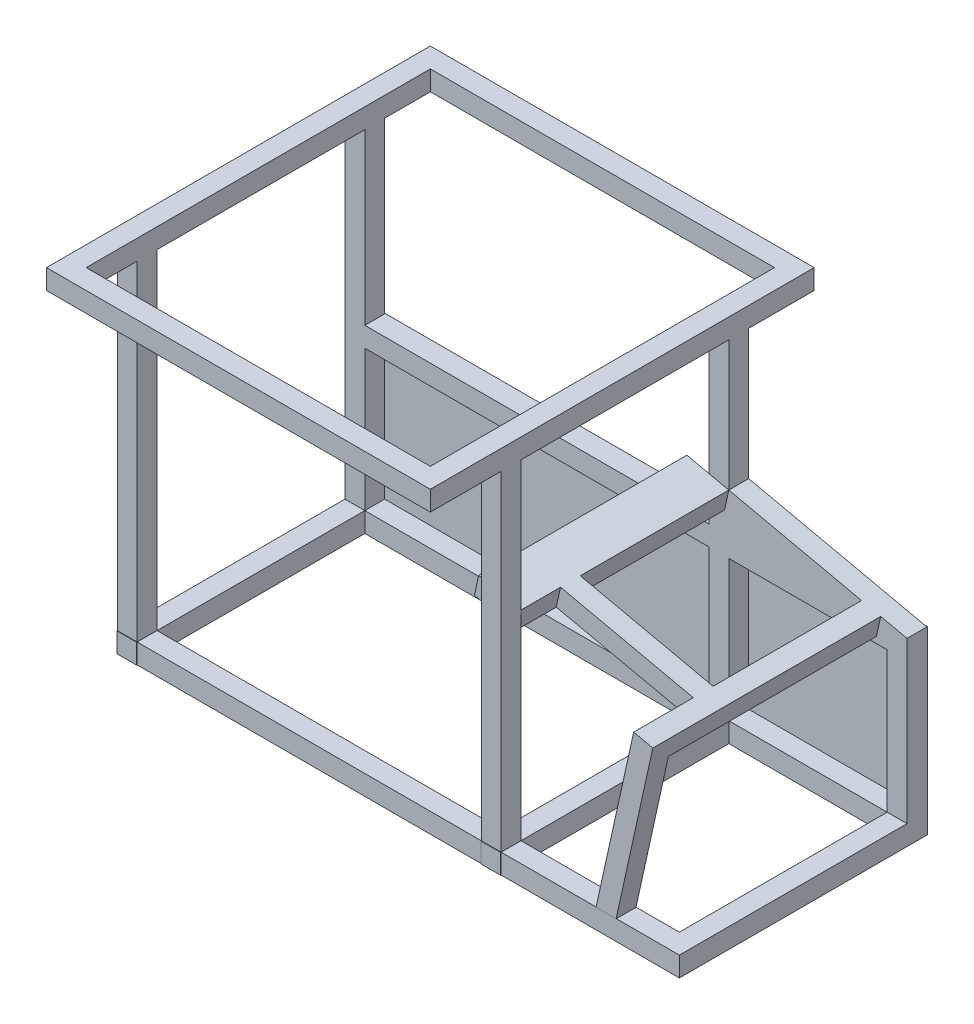
SolidWorks part; units mm, degrees
ref_plane "Front" through (0, 0, 0) normal (0, 0, 1) x (1, 0, 0)
ref_plane "Top" through (0, 0, 0) normal (0, 1, 0) x (1, 0, 0)
ref_plane "Right" through (0, 0, 0) normal (1, 0, 0) x (0, 0, -1)
sketch "Croquis1" plane through (0, 0, 0) normal (0, 1, 0) x (1, 0, 0)
  line L0 (-25.4, -25.4) -> (-25.4, 465.9875)
  line L1 (0, 0) -> (440.5875, 0)
  line L2 (0, 0) -> (0, 440.5875)
  line L3 (0, 440.5875) -> (440.5875, 440.5875)
  line L4 (440.5875, 0) -> (440.5875, 440.5875)
  line L5 (-25.4, 465.9875) -> (465.9875, 465.9875)
  line L6 (465.9875, -25.4) -> (465.9875, 465.9875)
  line L7 (-25.4, -25.4) -> (465.9875, -25.4)
  dimension "D2" = 440.5875
  dimension "D3" = 440.5875
  dimension "D1" = 25.4
extrude "Saliente-Extruir1" add sketch "Croquis1" against normal blind 25.4
sketch "Croquis2" plane through (0, -25.4, 0) normal (0, -1, 0) x (1, 0, 0)
  line L10 (-25.4, -382.0875) -> (465.9875, -382.0875) construction
  line L11 (465.9875, -382.0875) -> (440.5875, -382.0875)
  line L12 (465.9875, -382.0875) -> (465.9875, -356.6875)
  line L13 (465.9875, -356.6875) -> (440.5875, -356.6875)
  line L14 (440.5875, -382.0875) -> (440.5875, -356.6875)
  line L15 (-25.4, -356.6875) -> (0, -356.6875)
  line L16 (-25.4, -356.6875) -> (-25.4, -382.0875)
  line L17 (-25.4, -382.0875) -> (0, -382.0875)
  line L18 (0, -356.6875) -> (0, -382.0875)
  line L19 (-25.4, -465.9875) -> (-25.4, 25.4) construction
  line L20 (465.9875, 25.4) -> (465.9875, -465.9875) construction
  dimension "D1" = 25.4
extrude "Saliente-Extruir2" add sketch "Croquis2" along normal up to surface (422.3129 mm away)
sketch "Croquis3" plane through (0, -447.7129, 0) normal (0, -1, 0) x (1, 0, 0)
  line L1 (-25.4, -382.0875) -> (0, -382.0875)
  line L2 (-25.4, -382.0875) -> (-25.4, -356.6875)
  line L3 (-25.4, -356.6875) -> (0, -356.6875)
  line L4 (0, -382.0875) -> (0, -356.6875)
  line L5 (465.9875, -382.0875) -> (440.5875, -382.0875)
  line L6 (465.9875, -382.0875) -> (465.9875, -356.6875)
  line L7 (465.9875, -356.6875) -> (440.5875, -356.6875)
  line L8 (440.5875, -382.0875) -> (440.5875, -356.6875)
  line L14 (-25.4, -382.0875) -> (465.9875, -382.0875) construction
extrude "Saliente-Extruir3" add sketch "Croquis3" along normal blind 25.4
sketch "Croquis4" plane through (0, 0, 0) normal (1, 0, 0) x (0, 0, -1)
  line L0 (382.0875, -473.1129) -> (382.0875, -25.4) construction
  line L1 (356.6875, -473.1129) -> (382.0875, -473.1129)
  line L2 (356.6875, -473.1129) -> (356.6875, -447.7129)
  line L3 (356.6875, -447.7129) -> (382.0875, -447.7129)
  line L4 (382.0875, -473.1129) -> (382.0875, -447.7129)
  dimension "D1" = 25.4
extrude "Saliente-Extruir4" add sketch "Croquis4" along normal up to next
sketch "Croquis5" plane through (0, 0, -356.6875) normal (0, 0, 1) x (1, 0, 0)
  line L1 (0, -447.7129) -> (-25.4, -447.7129)
  line L2 (0, -447.7129) -> (0, -473.1129)
  line L3 (0, -473.1129) -> (-25.4, -473.1129)
  line L4 (-25.4, -447.7129) -> (-25.4, -473.1129)
  line L5 (440.5875, -447.7129) -> (465.9875, -447.7129)
  line L6 (440.5875, -447.7129) -> (440.5875, -473.1129)
  line L7 (440.5875, -473.1129) -> (465.9875, -473.1129)
  line L8 (465.9875, -447.7129) -> (465.9875, -473.1129)
extrude "Saliente-Extruir5" add sketch "Croquis5" along normal blind 292
sketch "Croquis6" plane through (440.5875, 0, 0) normal (-1, 0, 0) x (0, 0, 1)
  line L2 (0, -399) -> (25.4, -399)
  line L3 (0, -399) -> (0, -424.4)
  line L4 (0, -424.4) -> (25.4, -424.4)
  line L5 (25.4, -399) -> (25.4, -424.4)
sketch "Croquis7" plane through (0, 0, 0) normal (1, 0, 0) x (0, 0, -1)
  line L0 (356.6875, -447.7129) -> (356.6875, -25.4) construction
  line L1 (356.6875, -267.7129) -> (382.0875, -267.7129)
  line L2 (356.6875, -267.7129) -> (356.6875, -242.3129)
  line L3 (356.6875, -242.3129) -> (382.0875, -242.3129)
  line L4 (382.0875, -267.7129) -> (382.0875, -242.3129)
  line L5 (382.0875, -447.7129) -> (382.0875, -25.4) construction
  line L6 (382.0875, -447.7129) -> (356.6875, -447.7129) construction
  dimension "D1" = 25.4
  dimension "D2" = 180
extrude "Saliente-Extruir7" add sketch "Croquis7" along normal up to next
sketch "Croquis9" plane through (0, -447.7129, 0) normal (0, 1, 0) x (1, 0, 0)
  line L0 (465.9875, 382.0875) -> (694.1478, 382.0875)
  line L1 (694.1478, 382.0875) -> (694.1478, 65.2424)
  line L2 (694.1478, 65.2424) -> (465.9875, 65.2424)
  line L3 (465.9875, 64.6875) -> (465.9875, 356.6875) construction
  line L4 (465.9875, 356.6875) -> (668.7478, 356.6875)
  line L5 (668.7478, 356.6875) -> (668.7478, 90.6424)
  line L6 (668.7478, 90.6424) -> (465.9875, 90.6424)
  line L8 (465.9875, 356.6875) -> (465.9875, 382.0875)
  line L9 (465.9875, 90.6424) -> (0, 90.6424)
  line L10 (0, 440.5875) -> (0, 0) construction
  line L11 (0, 90.6424) -> (0, 65.2424)
  line L12 (0, 65.2424) -> (465.9875, 65.2424)
  dimension "D1" = 25.4
extrude "Saliente-Extruir9" add sketch "Croquis9" against normal blind 25.4
sketch "Croquis10" plane through (0, 0, -356.6875) normal (0, 0, 1) x (1, 0, 0)
  line L0 (668.7478, -447.7129) -> (668.7478, -267.7129)
  line L1 (668.7478, -267.7129) -> (465.9875, -267.7129)
  line L2 (465.9875, -267.7129) -> (465.9875, -191.9475)
  line L3 (465.9875, -447.7129) -> (465.9875, -25.4) construction
  line L4 (465.9875, -191.9475) -> (694.1478, -242.3129)
  line L5 (694.1478, -242.3129) -> (694.1478, -447.7129)
  line L6 (694.1478, -447.7129) -> (668.7478, -447.7129)
extrude "Saliente-Extruir10" add sketch "Croquis10" against normal blind 25.4
sketch "Croquis11" plane through (0, -447.7129, 0) normal (0, 1, 0) x (1, 0, 0)
  line L0 (-25.4, 64.6875) -> (-25.4, 356.6875) construction
  line L1 (0, 65.2424) -> (-25.4, 65.2424)
  line L2 (0, 65.2424) -> (0, 90.6424)
  line L3 (0, 90.6424) -> (-25.4, 90.6424)
  line L4 (-25.4, 65.2424) -> (-25.4, 90.6424)
  line L6 (465.9875, 90.6424) -> (440.5875, 90.6424)
  line L7 (465.9875, 90.6424) -> (465.9875, 65.2424)
  line L8 (465.9875, 65.2424) -> (440.5875, 65.2424)
  line L9 (440.5875, 90.6424) -> (440.5875, 65.2424)
extrude "Saliente-Extruir11" add sketch "Croquis11" along normal up to next
sketch "Croquis12" plane through (-18.7509, -84.9438, 0) normal (0.2156, 0.9765, 0) x (0.9765, -0.2156, 0)
  line L0 (670.4446, 356.6875) -> (670.4446, 166.5589)
  line L1 (730.0614, 356.6875) -> (496.4083, 356.6875) construction
  line L2 (670.4446, 166.5589) -> (496.4083, 166.5589)
  line L3 (496.4083, 166.5589) -> (496.4083, 356.6875)
  line L4 (496.4083, 356.6875) -> (441.4736, 356.6875)
  line L5 (441.4736, 356.6875) -> (441.4736, 90.0989)
  line L6 (441.4736, 90.0989) -> (496.4083, 90.0989)
  line L7 (496.4083, 90.0989) -> (496.4083, 141.2624)
  line L8 (496.4083, 141.2624) -> (670.4446, 141.2624)
  line L9 (670.4446, 141.2624) -> (670.4446, 64.9507)
  line L10 (670.4446, 64.9507) -> (695.5318, 64.9507)
  line L11 (695.5318, 64.9507) -> (695.5318, 356.6875)
  line L12 (670.4446, 356.6875) -> (695.5318, 356.6875)
extrude "Saliente-Extruir12" add sketch "Croquis12" against normal blind 25.4
sketch "Croquis13" plane through (-24.2261, -109.7466, 0) normal (-0.2156, -0.9765, 0) x (0.9765, -0.2156, 0)
  line L0 (670.4446, -141.2624) -> (670.4446, -64.9507) construction
  line L1 (695.5318, -64.9507) -> (670.4446, -64.9507)
  line L2 (695.5318, -64.9507) -> (695.5318, -90.3507)
  line L3 (695.5318, -90.3507) -> (670.4446, -90.3507)
  line L4 (670.4446, -64.9507) -> (670.4446, -90.3507)
  dimension "D1" = 25.4
extrude "Saliente-Extruir13" add sketch "Croquis13" along normal up to surface (192.5672 mm away)
sketch "Croquis8" plane through (0, 0, -382.0875) normal (0, 0, -1) x (-1, 0, 0)
  line L0 (25.4, -473.1129) -> (-694.1478, -473.1129) construction
  line L1 (-465.9875, -473.1129) -> (25.4, -473.1129)
  line L3 (-465.9875, -242.3129) -> (25.4, -242.3129)
  line L4 (25.4, -473.1129) -> (25.4, -242.3129)
  line L5 (-465.9875, -424.4) -> (-465.9875, -25.4) construction
  line L6 (25.4, -424.4) -> (25.4, -25.4) construction
  line L8 (-694.1478, -242.3129) -> (-465.9875, -242.3129)
  line L9 (-694.1478, -242.3129) -> (-694.1478, -473.1129)
  line L10 (-694.1478, -473.1129) -> (-465.9875, -473.1129)
extrude "Saliente-Extruir8" add sketch "Croquis8" along normal blind 0.7937
